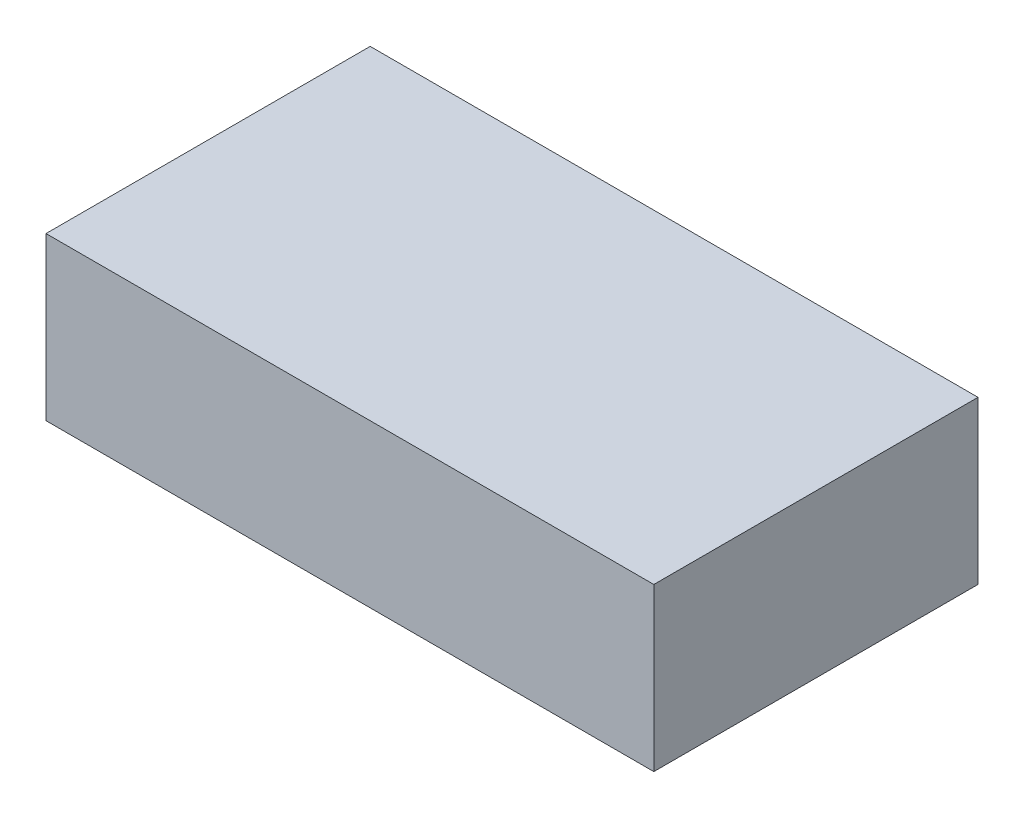
SolidWorks part; units mm, degrees
material "Beech"
ref_plane "Front Plane" through (0, 0, 0) normal (0, 0, 1) x (1, 0, 0)
ref_plane "Top Plane" through (0, 0, 0) normal (0, 1, 0) x (1, 0, 0)
ref_plane "Right Plane" through (0, 0, 0) normal (1, 0, 0) x (0, 0, -1)
sketch "Sketch1" plane through (0, 0, 0) normal (0, 1, 0) x (1, 0, 0)
  line L1 (0, 0) -> (304.8, 0)
  line L2 (0, 0) -> (0, 304.8)
  line L3 (0, 304.8) -> (304.8, 304.8)
  line L4 (304.8, 0) -> (304.8, 304.8)
  dimension "D1" = 304.8
  dimension "D2" = 304.8
extrude "Boss-Extrude1" add sketch "Sketch1" along normal blind 6.35
sketch "Sketch2" plane through (0, 6.35, 0) normal (0, 1, 0) x (1, 0, 0)
  line L1 (304.8, 304.8) -> (0, 304.8) construction
  line L2 (23.8125, 304.8) -> (23.8125, 292.1)
  line L3 (23.8125, 292.1) -> (0, 292.1)
  line L4 (0, 304.8) -> (0, 0) construction
  line L6 (0, 292.1) -> (0, 0)
  line L7 (0, 0) -> (304.8, 0)
  line L8 (304.8, 0) -> (304.8, 304.8)
  line L9 (304.8, 304.8) -> (23.8125, 304.8)
  dimension "D1" = 23.8125
  dimension "D2" = 12.7
extrude "Cut-Extrude2" cut sketch "Sketch2" against normal blind 6.35 contours L3 L6 L7 L8 L9 L2
